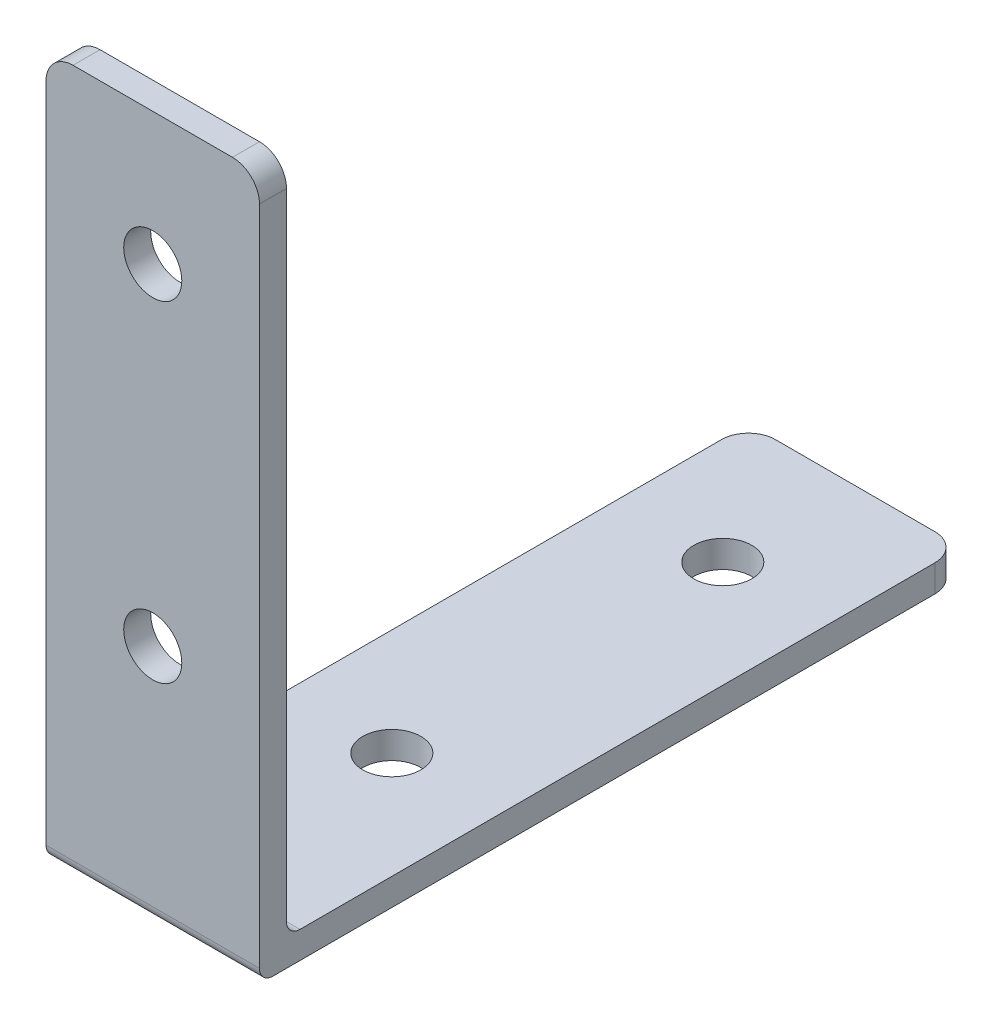
SolidWorks part; units mm, degrees
ref_plane "前基準面" through (0, 0, 0) normal (0, 0, 1) x (1, 0, 0)
ref_plane "上基準面" through (0, 0, 0) normal (0, 1, 0) x (1, 0, 0)
ref_plane "右基準面" through (0, 0, 0) normal (1, 0, 0) x (0, 0, -1)
sketch "草圖1" plane through (0, 0, 0) normal (0, 0, 1) x (1, 0, 0)
  line L1 (7.9, -1) -> (-7.9, -1)
  line L2 (7.9, -1) -> (7.9, 1)
  line L3 (7.9, 1) -> (-7.9, 1)
  line L4 (-7.9, -1) -> (-7.9, 1)
  line L5 (7.9, -1) -> (-7.9, 1) construction
  line L6 (7.9, 1) -> (-7.9, -1) construction
  point P0 (0, 0)
  dimension "D1" = 15.8
  dimension "D2" = 2
extrude "填料-伸長1" add sketch "草圖1" along normal blind 52
sketch "草圖2" plane through (0, 1, 0) normal (0, 1, 0) x (1, 0, 0)
  line L0 (7.9, -52) -> (7.9, 0) construction
  line L1 (-7.9, -52) -> (7.9, -52)
  line L2 (-7.9, -52) -> (-7.9, -50)
  line L3 (-7.9, -50) -> (7.9, -50)
  line L4 (7.9, -52) -> (7.9, -50)
  dimension "D1" = 2
extrude "填料-伸長2" add sketch "草圖2" along normal blind 50
fillet "圓角5" radius 1 1 edges at (0, -1, 52)
fillet "圓角6" radius 1 1 edges at (0, 1, 50)
fillet "圓角7" radius 2 1 edges at (7.9, 51, 51)
fillet "圓角8" radius 2 3 edges at (7.9, 0, 0) (-7.9, 0, 0) (-7.9, 51, 51)
sketch "草圖3" plane through (0, 0, 50) normal (0, 0, -1) x (-1, 0, 0)
  line L0 (0, 51) -> (0, 41.2) construction
  line L1 (-5.9, 51) -> (5.9, 51) construction
  line L2 (0, 41.2) -> (0, 16.7) construction
  circle A0 centre (0, 41.2) radius 2.15
  circle A1 centre (0, 16.7) radius 2.15
  dimension "D2" = 4.3
  dimension "D4" = 4.3
  dimension "D1" = 9.8
  dimension "D3" = 24.5
extrude "除料-伸長1" cut sketch "草圖3" against normal blind 50
sketch "草圖8" plane through (0, 1, 0) normal (0, 1, 0) x (1, 0, 0)
  line L0 (0, 0) -> (0, -9.8) construction
  line L1 (0, -9.8) -> (0, -34.3) construction
  circle A0 centre (0, -9.8) radius 2.15
  circle A1 centre (0, -34.3) radius 2.15
  dimension "D2" = 4.3
  dimension "D4" = 4.3
  dimension "D1" = 9.8
  dimension "D3" = 24.5
extrude "除料-伸長3" cut sketch "草圖8" against normal blind 50
